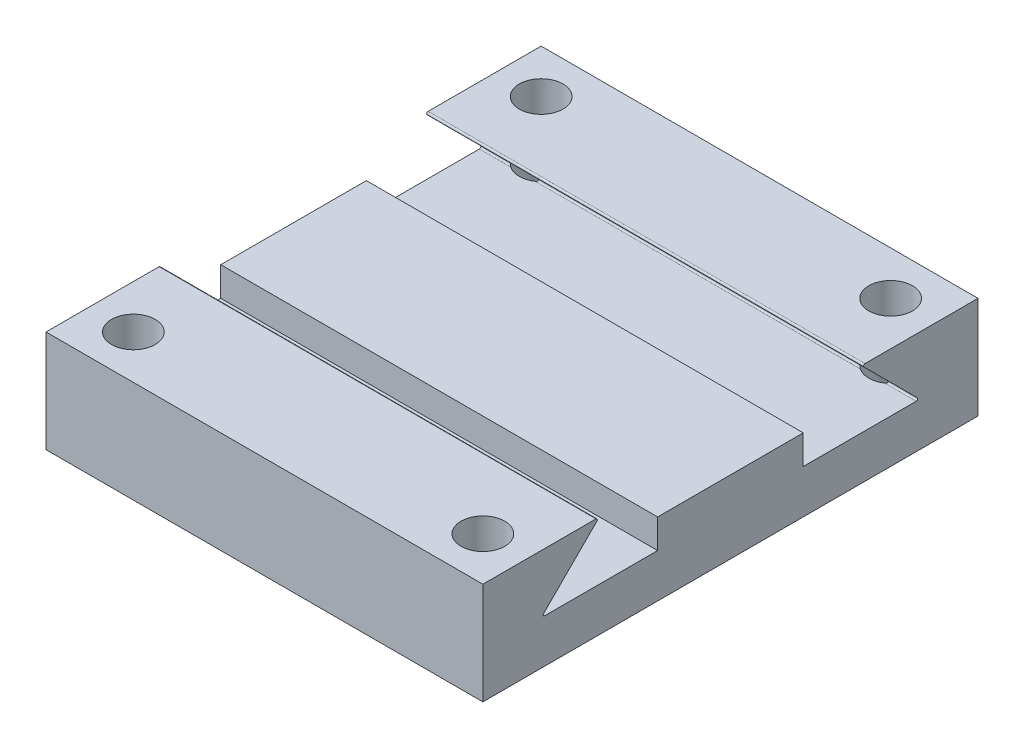
SolidWorks part; units mm, degrees
ref_plane "Front" through (0, 0, 0) normal (0, 0, 1) x (1, 0, 0)
ref_plane "Top" through (0, 0, 0) normal (0, 1, 0) x (1, 0, 0)
ref_plane "Right" through (0, 0, 0) normal (1, 0, 0) x (0, 0, -1)
sketch "Sketch1" plane through (0, 0, 0) normal (0, 1, 0) x (1, 0, 0)
  line L1 (-15, -17) -> (15, -17)
  line L2 (-15, -17) -> (-15, 17)
  line L3 (-15, 17) -> (15, 17)
  line L4 (15, -17) -> (15, 17)
  line L5 (-15, -17) -> (15, 17) construction
  line L6 (-15, 17) -> (15, -17) construction
  point P0 (0, 0)
  dimension "D1" = 30
  dimension "D2" = 34
extrude "Boss-Extrude1" add sketch "Sketch1" along normal blind 3
sketch "Sketch2" plane through (0, 3, 0) normal (0, 1, 0) x (1, 0, 0)
  line L1 (-15, -17) -> (15, -17)
  line L2 (-15, -17) -> (-15, -9)
  line L3 (-15, -9) -> (15, -9)
  line L4 (15, -17) -> (15, -9)
  line L5 (-15, -17) -> (15, -9) construction
  line L6 (-15, -9) -> (15, -17) construction
  line L7 (15, -17) -> (15, 17) construction
  line L8 (-15, 9) -> (15, 9)
  line L9 (-15, 9) -> (-15, 17)
  line L10 (-15, 17) -> (15, 17)
  line L11 (15, 9) -> (15, 17)
  line L12 (-15, 9) -> (15, 17) construction
  line L13 (-15, 17) -> (15, 9) construction
  point P0 (0, -13)
  point P9 (0, 13)
  dimension "D1" = 13
  dimension "D2" = 8
  dimension "D3" = 2
extrude "Boss-Extrude2" add sketch "Sketch2" along normal blind 4
sketch "Sketch4" plane through (15, 0, 0) normal (1, 0, 0) x (0, 0, -1)
  line L0 (-9, 3) -> (-13, 3)
  line L1 (-13, 3) -> (-9, 7)
  line L3 (-9, 7) -> (-9, 3)
  line L5 (9, 3) -> (13, 3)
  line L6 (9, 3) -> (9, 7)
  line L8 (9, 7) -> (13, 3)
  dimension "D1" = 4
  dimension "D2" = 4
extrude "Cut-Extrude2" cut sketch "Sketch4" against normal blind 30
fillet "Fillet4" radius 0.1 1 edges at (0, 7, 9)
fillet "Fillet5" radius 0.1 2 edges at (0, 3, 13)
fillet "Fillet6" radius 0.1 2 edges at (0, 3, -13)
fillet "Fillet7" radius 0.1 1 edges at (0, 7, -9)
sketch "Sketch5" plane through (0, 7, 0) normal (0, 1, 0) x (1, 0, 0)
  line L1 (-15, 9.2414) -> (15, 9.2414) construction
  circle A0 centre (-12, 14) radius 1.5
  circle A1 centre (12, 14) radius 1.5
  circle A2 centre (-12, -14) radius 1.5
  circle A3 centre (12, -14) radius 1.5
  point P2 (0, 9.2414)
  dimension "D2" = 3
  dimension "D1" = 14
  dimension "D3" = 12
  dimension "D4" = 2
  dimension "D5" = 2
extrude "Cut-Extrude3" cut sketch "Sketch5" against normal blind 30
sketch "Sketch7" plane through (0, 3, 0) normal (0, 1, 0) x (1, 0, 0)
  line L0 (15, -12.3593) -> (15, 12.3548) construction
  line L1 (-15, -5) -> (15, -5)
  line L2 (-15, -5) -> (-15, 5)
  line L3 (-15, 5) -> (15, 5)
  line L4 (15, -5) -> (15, 5)
  line L5 (-15, -5) -> (15, 5) construction
  line L6 (-15, 5) -> (15, -5) construction
  point P0 (0, 0)
  dimension "D1" = 10
extrude "Boss-Extrude3" add sketch "Sketch7" along normal blind 2
